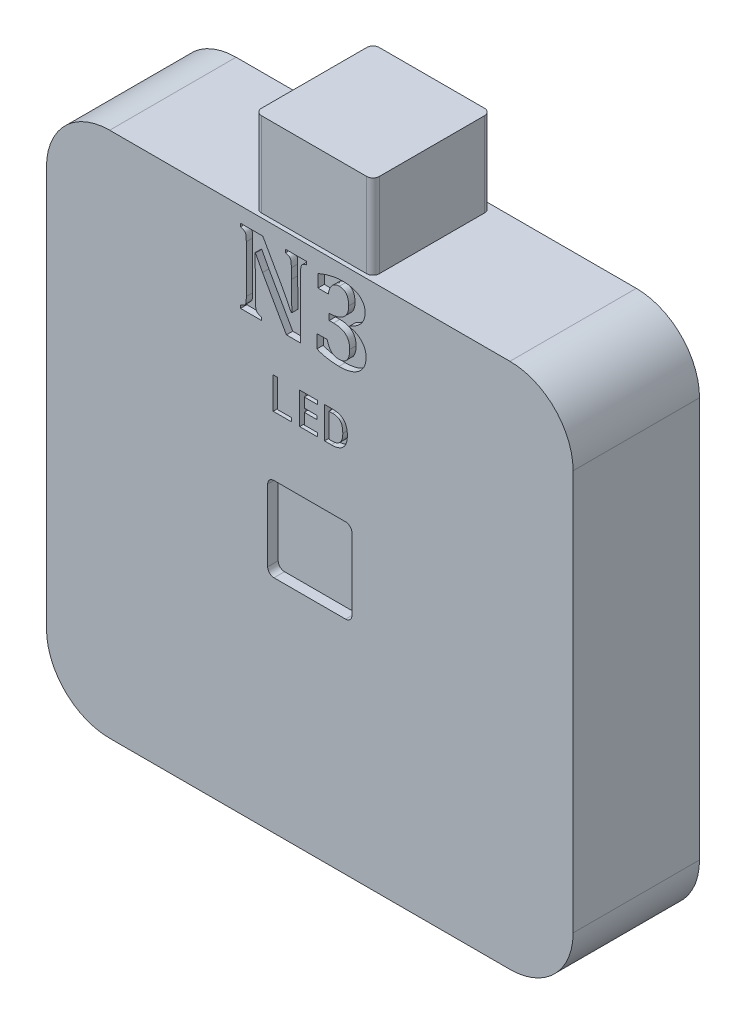
SolidWorks part; units mm, degrees
ref_plane "前视基准面" through (0, 0, 0) normal (0, 0, 1) x (1, 0, 0)
ref_plane "上视基准面" through (0, 0, 0) normal (0, 1, 0) x (1, 0, 0)
ref_plane "右视基准面" through (0, 0, 0) normal (1, 0, 0) x (0, 0, -1)
sketch "Main" plane through (0, 0, 0) normal (0, 0, 1) x (1, 0, 0)
  line L0 (-12.5, 9.5) -> (-12.5, -9.5)
  line L1 (0, 0) -> (30.1154, 0) construction
  line L2 (0, -7.3749) -> (0, 9.6594) construction
  line L3 (-9.5, 12.5) -> (9.5, 12.5)
  line L4 (12.5, 9.5) -> (12.5, -9.5)
  line L5 (-9.5, -12.5) -> (9.5, -12.5)
  arc A0 (-12.5, 9.5) -> (-9.5, 12.5) centre (-9.5, 9.5) cw
  arc A1 (12.5, 9.5) -> (9.5, 12.5) centre (9.5, 9.5) ccw
  arc A2 (12.5, -9.5) -> (9.5, -12.5) centre (9.5, -9.5) cw
  arc A3 (-12.5, -9.5) -> (-9.5, -12.5) centre (-9.5, -9.5) ccw
  point P4 (0, 0)
  point P6 (-12.5, 0)
  point P7 (-2.5, 2.5)
  point P9 (-2.5, 2.5)
  point P12 (0, 12.5)
  point P15 (0, 0)
  point P16 (0, 0)
  point P17 (-2.5, 12.5)
  point P18 (0, 0)
  dimension "D2" = 3
  dimension "D1" = 12.5
  dimension "D4" = 12.5
extrude "凸台-拉伸1" add sketch "Main" along normal mid plane 6
sketch "LED" plane through (0, 0, 3) normal (0, 0, 1) x (1, 0, 0)
  line L0 (-2, 1.7) -> (-2, -1.7)
  line L1 (0, 0) -> (0, 2.0647) construction
  line L2 (0, 0) -> (2.1929, 0) construction
  line L3 (1.7, 2) -> (-1.7, 2)
  line L4 (1.7, -2) -> (-1.7, -2)
  line L5 (2, 1.7) -> (2, -1.7)
  arc A1 (-2, 1.7) -> (-1.7, 2) centre (-1.7, 1.7) cw
  arc A2 (-1.7, -2) -> (-2, -1.7) centre (-1.7, -1.7) cw
  arc A3 (1.7, 2) -> (2, 1.7) centre (1.7, 1.7) cw
  arc A4 (1.7, -2) -> (2, -1.7) centre (1.7, -1.7) ccw
  point P14 (-2, 0)
  point P21 (0, -2)
  point P23 (0, 2)
  dimension "D4" = 0.3
  dimension "D1" = 2
  dimension "D2" = 2
extrude "切除-拉伸2" cut sketch "LED" against normal blind 0.5
sketch "草图3" plane through (0, 0, 3) normal (0, 0, 1) x (1, 0, 0)
  line L0 (0, 0) -> (18.2534, 0) construction
  line L1 (0, 0) -> (0, 13.6083) construction
  text T0 "N3" font "Cambria" height 3.5
  text T1 "LED" font "Consolas" height 1.5
  dimension "D1" = 3.55
  dimension "D2" = 2
extrude "切除-拉伸3" cut sketch "草图3" against normal blind 0.3
sketch "草图4" plane through (0, 12.5, 0) normal (0, 1, 0) x (1, 0, 0)
  line L1 (-2.5, 2.8) -> (2.5, 2.8)
  line L2 (-2.8, 2.5) -> (-2.8, -2.5)
  line L3 (-2.5, -2.8) -> (2.5, -2.8)
  line L4 (2.8, 2.5) -> (2.8, -2.5)
  arc A0 (-2.8, 2.5) -> (-2.5, 2.8) centre (-2.5, 2.5) cw
  arc A1 (-2.8, -2.5) -> (-2.5, -2.8) centre (-2.5, -2.5) ccw
  arc A2 (2.8, -2.5) -> (2.5, -2.8) centre (2.5, -2.5) cw
  arc A3 (2.8, 2.5) -> (2.5, 2.8) centre (2.5, 2.5) ccw
  dimension "D3" = 0.3
  dimension "D1" = 2.8
  dimension "D2" = 2.8
  dimension "D4" = 5.6
  dimension "D5" = 5.6
extrude "凸台-拉伸2" add sketch "草图4" along normal blind 4
sketch "草图5" plane through (0, -12.5, 0) normal (0, -1, 0) x (1, 0, 0)
  line L0 (-14.5459, 0) -> (14.5459, 0) construction
  line L1 (0, 8.6152) -> (0, -8.7884) construction
  line L2 (-3.25, -0.8) -> (3.25, -0.8)
  line L3 (-2.5, 1.2) -> (2.5, 1.2)
  line L4 (-3.25, -0.8) -> (-3.25, 0)
  line L5 (3.25, -0.8) -> (3.25, 0)
  line L6 (-2.5, 1.2) -> (-3.25, 0)
  line L7 (2.5, 1.2) -> (3.25, 0)
  point P7 (0, -0.8)
  point P10 (0, 1.2)
  dimension "D1" = 6.5
  dimension "D2" = 5
  dimension "D3" = 2
  dimension "D4" = 0.8
extrude "切除-拉伸4" cut sketch "草图5" against normal blind 5
